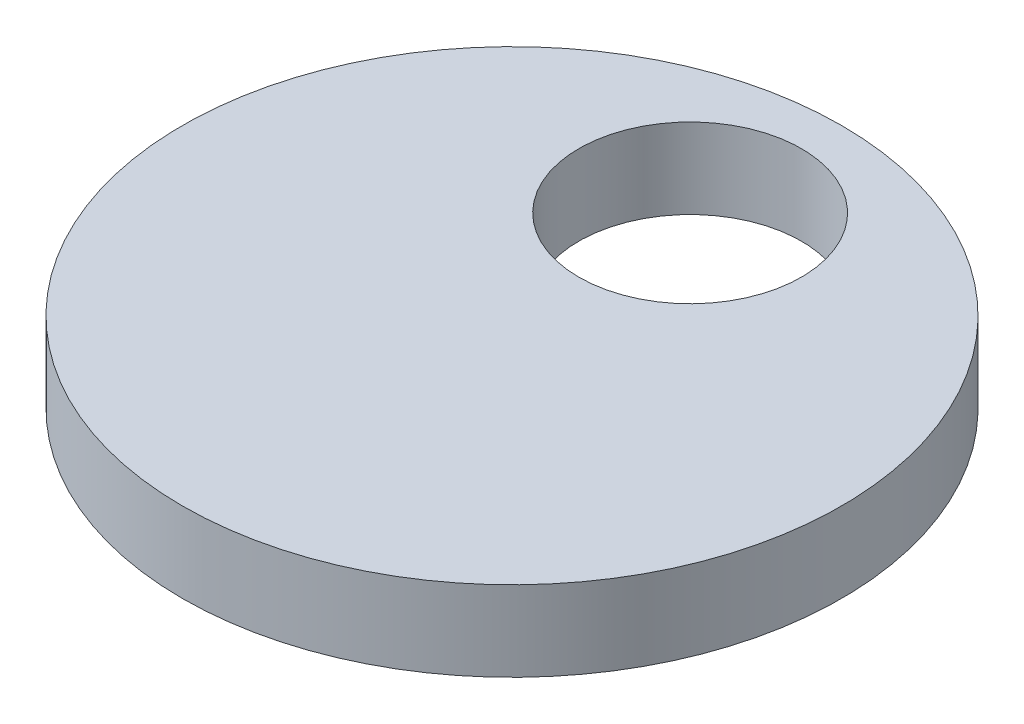
SolidWorks part; units mm, degrees
ref_plane "Front Plane" through (0, 0, 0) normal (0, 0, 1) x (1, 0, 0)
ref_plane "Top Plane" through (0, 0, 0) normal (0, 1, 0) x (1, 0, 0)
ref_plane "Right Plane" through (0, 0, 0) normal (1, 0, 0) x (0, 0, -1)
sketch "Sketch1" plane through (0, 0, 0) normal (0, 1, 0) x (1, 0, 0)
  circle A0 centre (0, 0) radius 7.4
  dimension "D1" = 14.8
extrude "Boss-Extrude1" add sketch "Sketch1" along normal blind 1.8
sketch "Sketch2" plane through (0, 1.8, 0) normal (0, 1, 0) x (1, 0, 0)
  circle A0 centre (0, 4) radius 2.5
  dimension "D1" = 5
  dimension "D2" = 4
extrude "Cut-Extrude1" cut sketch "Sketch2" against normal blind 1.8
